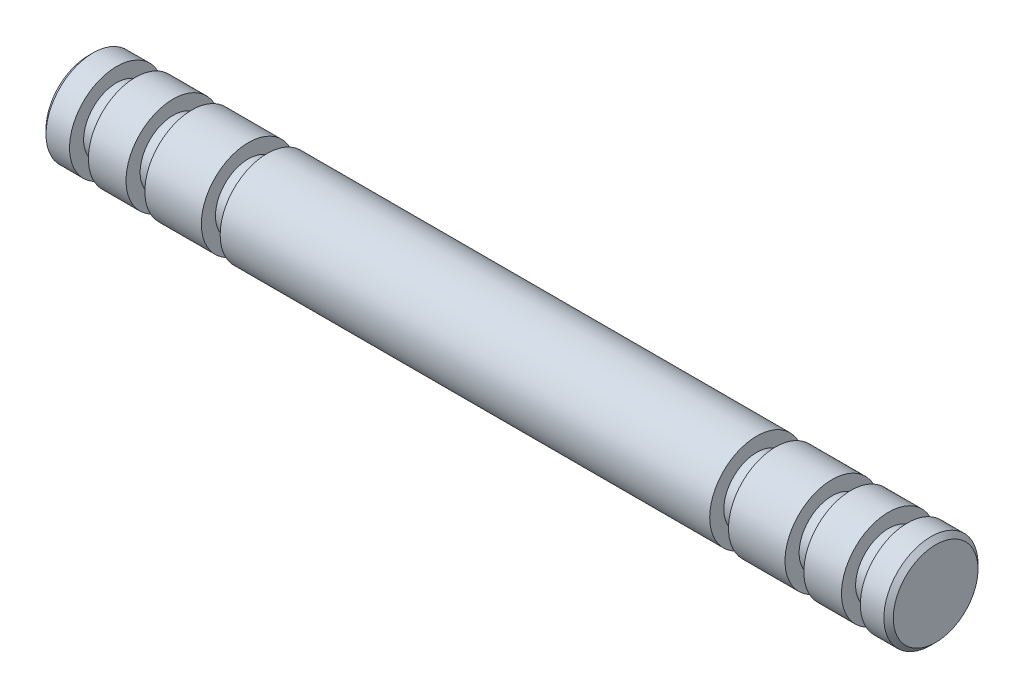
SolidWorks part; units mm, degrees
ref_plane "前视基准面" through (0, 0, 0) normal (0, 0, 1) x (1, 0, 0)
ref_plane "上视基准面" through (0, 0, 0) normal (0, 1, 0) x (1, 0, 0)
ref_plane "右视基准面" through (0, 0, 0) normal (1, 0, 0) x (0, 0, -1)
sketch "草图1" plane through (0, 0, 0) normal (1, 0, 0) x (0, 0, -1)
  circle A0 centre (0, 0) radius 5
  dimension "D1" = 10
extrude "凸台-拉伸1" add sketch "草图1" along normal blind 52
sketch "草图2" plane through (52, 0, 0) normal (1, 0, 0) x (0, 0, -1)
  circle A0 centre (0, 0) radius 3.5
  dimension "D1" = 7
extrude "凸台-拉伸2" add sketch "草图2" along normal blind 2
sketch "草图3" plane through (54, 0, 0) normal (1, 0, 0) x (0, 0, -1)
  circle A0 centre (0, 0) radius 5
  dimension "D1" = 10
extrude "凸台-拉伸3" add sketch "草图3" along normal blind 14
sketch "草图4" plane through (68, 0, 0) normal (1, 0, 0) x (0, 0, -1)
  circle A0 centre (0, 0) radius 5
  dimension "D1" = 10
extrude "凸台-拉伸4" add sketch "草图4" along normal blind 2
sketch "草图5" plane through (70, 0, 0) normal (1, 0, 0) x (0, 0, -1)
  circle A0 centre (0, 0) radius 5
  dimension "D1" = 10
extrude "凸台-拉伸5" add sketch "草图5" along normal blind 4
sketch "草图6" plane through (74, 0, 0) normal (1, 0, 0) x (0, 0, -1)
  circle A0 centre (0, 0) radius 5
  dimension "D1" = 10
extrude "凸台-拉伸6" add sketch "草图6" along normal blind 2
sketch "草图7" plane through (76, 0, 0) normal (1, 0, 0) x (0, 0, -1)
  circle A0 centre (0, 0) radius 5
  dimension "D1" = 10
extrude "凸台-拉伸7" add sketch "草图7" along normal blind 10
sketch "草图8" plane through (0, 0, 0) normal (-1, 0, 0) x (0, 0, 1)
  circle A0 centre (0, 0) radius 3.5
  dimension "D1" = 7
extrude "凸台-拉伸8" add sketch "草图8" along normal blind 2
sketch "草图9" plane through (-2, 0, 0) normal (-1, 0, 0) x (0, 0, 1)
  circle A0 centre (0, 0) radius 5
  dimension "D1" = 10
extrude "凸台-拉伸9" add sketch "草图9" along normal blind 14
sketch "草图10" plane through (-16, 0, 0) normal (-1, 0, 0) x (0, 0, 1)
  circle A0 centre (0, 0) radius 5
  dimension "D1" = 10
extrude "凸台-拉伸10" add sketch "草图10" along normal blind 2
sketch "草图11" plane through (-18, 0, 0) normal (-1, 0, 0) x (0, 0, 1)
  circle A0 centre (0, 0) radius 5
  dimension "D1" = 10
extrude "凸台-拉伸11" add sketch "草图11" along normal blind 4
sketch "草图12" plane through (-22, 0, 0) normal (-1, 0, 0) x (0, 0, 1)
  circle A0 centre (0, 0) radius 5
  dimension "D1" = 10
extrude "凸台-拉伸12" add sketch "草图12" along normal blind 2
sketch "草图13" plane through (-24, 0, 0) normal (-1, 0, 0) x (0, 0, 1)
  circle A0 centre (0, 0) radius 5
  dimension "D1" = 10
extrude "凸台-拉伸13" add sketch "草图13" along normal blind 10
chamfer "倒角1" distance 0.5 angle 45 2 edges at (-34, 0, 5) (86, 0, -5)
ref_plane "基准面1" through (-8, 0, 0) normal (1, 0, 0) x (0, 0, -1)
sketch "草图14" plane through (-8, 0, 0) normal (1, 0, 0) x (0, 0, -1)
  circle A0 centre (0, 0) radius 5
  circle A1 centre (0, 0) radius 3.5
  dimension "D1" = 7
extrude "切除-拉伸1" cut sketch "草图14" against normal blind 2
ref_plane "基准面2" through (-14, 0, 0) normal (1, 0, 0) x (0, 0, -1)
sketch "草图15" plane through (-14, 0, 0) normal (1, 0, 0) x (0, 0, -1)
  circle A0 centre (0, 0) radius 5
  circle A1 centre (0, 0) radius 3.5
  dimension "D1" = 7
extrude "切除-拉伸2" cut sketch "草图15" against normal blind 2
ref_plane "基准面3" through (26, 0, 0) normal (1, 0, 0) x (0, 0, -1)
mirror "镜向1" about plane through (26, 0, 0) normal (1, 0, 0) of "切除-拉伸1", "切除-拉伸2"
sketch "草图16" plane through (86, 0, 0) normal (1, 0, 0) x (0, 0, -1)
  circle A0 centre (0, 0) radius 5
extrude "切除-拉伸3" cut sketch "草图16" against normal blind 15
sketch "草图17" plane through (-34, 0, 0) normal (-1, 0, 0) x (0, 0, 1)
  circle A0 centre (0, 0) radius 5
extrude "切除-拉伸4" cut sketch "草图17" against normal blind 15
chamfer "倒角2" distance 0.5 angle 45 2 edges at (-19, 0, 5) (71, 0, -5)
